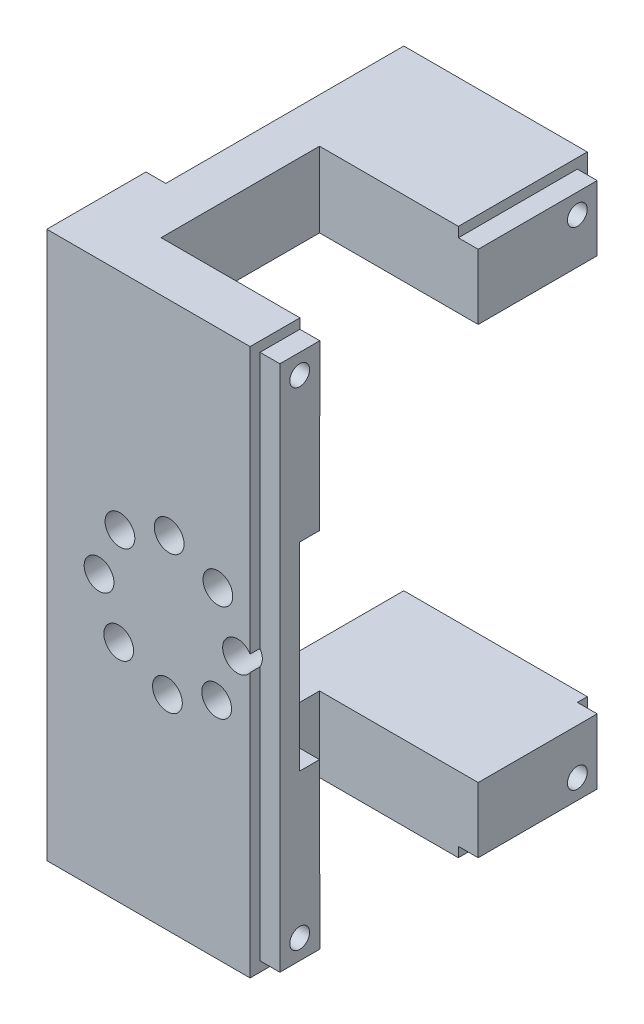
SolidWorks part; units mm, degrees
ref_plane "前视基准面" through (0, 0, 0) normal (0, 0, 1) x (1, 0, 0)
ref_plane "上视基准面" through (0, 0, 0) normal (0, 1, 0) x (1, 0, 0)
ref_plane "右视基准面" through (0, 0, 0) normal (1, 0, 0) x (0, 0, -1)
other "Configuration Table"
sketch "草图1" plane through (0, 0, 0) normal (0, 0, 1) x (1, 0, 0)
  line L0 (-1000, 0) -> (49000, 0) construction
  line L1 (-10.25, -20) -> (10.25, -20)
  line L2 (-10.25, -20) -> (-10.25, 20)
  line L3 (-10.25, 20) -> (10.25, 20)
  line L4 (10.25, -20) -> (10.25, 20)
  line L5 (-10.25, -20) -> (10.25, 20) construction
  line L6 (-10.25, 20) -> (10.25, -20) construction
  line L7 (-5, 15) -> (5, 15)
  line L8 (-5, 15) -> (-5, 25)
  line L9 (-5, 25) -> (5, 25)
  line L10 (5, 15) -> (5, 25)
  line L11 (-5, 15) -> (5, 25) construction
  line L12 (-5, 25) -> (5, 15) construction
  line L14 (-10.25, -35.1417) -> (10.25, -35.1417)
  line L15 (-10.25, -35.1417) -> (-10.25, 35.1417)
  line L16 (-10.25, 35.1417) -> (10.25, 35.1417)
  line L17 (10.25, -35.1417) -> (10.25, 35.1417)
  line L18 (-10.25, -35.1417) -> (10.25, 35.1417) construction
  line L19 (-10.25, 35.1417) -> (10.25, -35.1417) construction
  circle A0 centre (-5, 25) radius 2
  circle A1 centre (5, 25) radius 2
  circle A2 centre (5, -25) radius 2
  circle A3 centre (-5, -25) radius 2
  point P0 (0, 0)
  point P6 (0, 20)
  point P19 (0, 0)
  dimension "D5" = 4
  dimension "D6" = 4
  dimension "D1" = 20.5
  dimension "D2" = 40
  dimension "D3" = 10
  dimension "D4" = 10
extrude "凸台-拉伸1" add sketch "草图1" along normal blind 29 contours A1 L10 L3 L17 L16 L15 L8 A0 L9 | L14 L17 L1 L15 A2 A3 | A1 L9 A0 L8 L3 L10
sketch "草图2" plane through (0, 0, 29) normal (0, 0, 1) x (1, 0, 0)
  line L1 (-10.25, 35.1417) -> (10.25, 35.1417)
  line L2 (-10.25, 35.1417) -> (-10.25, -35.1417)
  line L3 (-10.25, -35.1417) -> (10.25, -35.1417)
  line L4 (10.25, 35.1417) -> (10.25, -35.1417)
extrude "凸台-拉伸2" add sketch "草图2" along normal blind 3
sketch "草图3" plane through (0, 0, 0) normal (0, 0, -1) x (-1, 0, 0)
  line L0 (-10.25, -35.1417) -> (-10.25, -20) construction
  line L1 (-10.25, -27.5709) -> (10.25, -27.5709)
  line L2 (-10.25, -27.5709) -> (-10.25, 27.5709)
  line L3 (-10.25, 27.5709) -> (10.25, 27.5709)
  line L4 (10.25, -27.5709) -> (10.25, 27.5709)
  line L5 (10.25, 20) -> (10.25, 35.1417) construction
  line L7 (-10.25, -35.1417) -> (10.25, -35.1417)
  line L8 (-10.25, -35.1417) -> (-10.25, 35.1417)
  line L9 (-10.25, 35.1417) -> (10.25, 35.1417)
  line L10 (10.25, -35.1417) -> (10.25, 35.1417)
  line M2 (-10.25, -35.1417) -> (10.25, -35.1417)
  line M3 (10.25, -35.1417) -> (10.25, -20)
  line M5 (-10.25, -20) -> (-10.25, -35.1417)
extrude "切除-拉伸1" cut sketch "草图3" against normal through all contours L1 M5 M2 M3 | L3 L10 L9 L8
sketch "草图5" plane through (0, -27.5709, 0) normal (0, -1, 0) x (1, 0, 0)
  line L0 (0, 0) -> (0, 2.5)
  circle A0 centre (0, 2.5) radius 2.5
  dimension "D2" = 5
  dimension "D1" = 2.5
extrude "凸台-拉伸3" add sketch "草图5" along normal blind 10
sketch "草图8" plane through (0, 27.5709, 0) normal (0, 1, 0) x (1, 0, 0)
  line L0 (0, 0) -> (0, -2.5)
  line L1 (0, -2.5) -> (0, -16.5)
  line L2 (0, -16.5) -> (0, -26.5)
  circle A0 centre (0, -16.5) radius 1.6
  circle A1 centre (0, -26.5) radius 1.6
  dimension "D4" = 3.2
  dimension "D5" = 3.2
  dimension "D1" = 2.5
  dimension "D2" = 14
  dimension "D3" = 10
extrude "切除-拉伸2" cut sketch "草图8" against normal up to next
sketch "草图9" plane through (0, -27.5709, 0) normal (0, -1, 0) x (1, 0, 0)
  line L1 (-10.25, 32) -> (10.25, 32)
  line L2 (-10.25, 32) -> (-10.25, 0)
  line L3 (-10.25, 0) -> (10.25, 0)
  line L4 (10.25, 32) -> (10.25, 0)
extrude "切除-拉伸3" cut sketch "草图9" along normal through all
sketch "草图12" plane through (0, 0, 0) normal (0, 0, -1) x (-1, 0, 0)
  line L1 (-10.25, 27.5709) -> (10.25, 27.5709)
  line L2 (-10.25, 27.5709) -> (-10.25, 20)
  line L3 (-10.25, 20) -> (10.25, 20)
  line L4 (10.25, 27.5709) -> (10.25, 20)
  circle A0 centre (-5, 25) radius 2
  circle A1 centre (5, 25) radius 2
extrude "凸台-拉伸5" add sketch "草图12" against normal blind 30
sketch "草图13" plane through (0, 27.5709, 0) normal (0, 1, 0) x (1, 0, 0)
  line L0 (0, 0) -> (0, -32)
  line L1 (10.25, -32) -> (-10.25, -32) construction
  line L2 (0, 0) -> (0, -10)
  line L3 (0, 0) -> (0, -2.5275)
  line L4 (0, 0) -> (0, -5)
  circle A2 centre (0, -5) radius 2.5
  circle A3 centre (0, -5) radius 4
  dimension "D3" = 5
  dimension "D4" = 5
  dimension "D5" = 8
  dimension "D1" = 32
  dimension "D2" = 10
extrude "凸台-拉伸6" add sketch "草图13" along normal blind 10 contours L4 A3 L2 A2 | L2 A3 L4 A2
sketch "草图15" plane through (0, 0, 0) normal (1, 0, 0) x (0, 0, -1)
  line L0 (-1, 27.5709) -> (0, 27.5709)
  line L1 (-1, 27.5709) -> (-1, 28.676)
  line L2 (-1, 27.5709) -> (-1, 37.5709) construction
  line L3 (-5, -962.4291) -> (-5, 49037.5709) construction
  line L4 (-2.5, 37.5709) -> (-7.5, 37.5709) construction
  arc A0 (-1, 28.676) -> (0, 27.5709) centre (0.1107, 28.676) ccw
  point P13 (-5, 37.5709)
revolve "旋转1" add sketch "草图15" angle 360 about L3
ref_plane "基准面1" through (0, 0, 5) normal (0, 0, 1) x (1, 0, 0)
sketch "草图16" plane through (0, 0, 5) normal (0, 0, 1) x (1, 0, 0)
  line L0 (0, 37.5709) -> (0, 33.5709)
  line L1 (2.5, 37.5709) -> (-2.5, 37.5709) construction
  circle A0 centre (0, 33.5709) radius 1.5
  dimension "D2" = 3
  dimension "D1" = 4
extrude "切除-拉伸5" cut sketch "草图16" against normal through all
sketch "草图17" plane through (0, 0, 0) normal (1, 0, 0) x (0, 0, -1)
  line L0 (-5, 37.5709) -> (-5, 33.5709)
  line L1 (-2.5, 37.5709) -> (-7.5, 37.5709) construction
  line L2 (-5, 11.275) -> (-5, -11.275) construction
  circle A0 centre (-5, 33.5709) radius 1.5
  dimension "D2" = 3
  dimension "D1" = 4
extrude "切除-拉伸6" cut sketch "草图17" against normal through all
sketch "草图19" plane through (0, -27.5709, 0) normal (0, -1, 0) x (1, 0, 0)
  line L0 (0, 0) -> (0, 5)
  line L1 (10.25, 0) -> (-10.25, 0) construction
  circle A0 centre (0, 5) radius 2.5
  circle A1 centre (0, 5) radius 4
  dimension "D2" = 5
  dimension "D3" = 8
  dimension "D1" = 5
extrude "凸台-拉伸7" add sketch "草图19" along normal blind 10
sketch "草图20" plane through (0, 0, 0) normal (1, 0, 0) x (0, 0, -1)
  line L0 (-1, -27.5709) -> (0, -27.5709)
  line L1 (-1, -27.5709) -> (-1, -28.5709)
  line L2 (-1, -37.5709) -> (-1, -27.5709) construction
  line L3 (-5, -1027.5709) -> (-5, 48972.4291) construction
  line L4 (-9, -27.5709) -> (-1, -27.5709) construction
  arc A0 (-1, -28.5709) -> (0, -27.5709) centre (0, -28.5709) cw
  point P13 (-5, -27.5709)
  dimension "D1" = 1
revolve "旋转2" add sketch "草图20" angle 360 about L3
sketch "草图21" plane through (0, 0, 5) normal (0, 0, 1) x (1, 0, 0)
  line L0 (0, -37.5709) -> (0, -33.5709)
  line L1 (-4, -37.5709) -> (4, -37.5709) construction
  circle A0 centre (0, -33.5709) radius 1.5
  dimension "D2" = 3
  dimension "D1" = 4
extrude "切除-拉伸7" cut sketch "草图21" against normal through all
sketch "草图22" plane through (0, 0, 0) normal (1, 0, 0) x (0, 0, -1)
  line L0 (-5, -37.5709) -> (-5, -33.5709)
  line L1 (-9, -37.5709) -> (-1, -37.5709) construction
  line L2 (-5, 11.275) -> (-5, -11.275) construction
  circle A0 centre (-5, -33.5709) radius 1.5
  dimension "D2" = 3
  dimension "D1" = 4
extrude "切除-拉伸8" cut sketch "草图22" against normal through all
sketch "草图23" plane through (0, 0, 32) normal (0, 0, 1) x (1, 0, 0)
  line L1 (-10.25, 27.5709) -> (10.25, 27.5709)
  line L2 (-10.25, 27.5709) -> (-10.25, -27.5709)
  line L3 (-10.25, -27.5709) -> (10.25, -27.5709)
  line L4 (10.25, 27.5709) -> (10.25, -27.5709)
extrude "凸台-拉伸8" add sketch "草图23" along normal blind 2
sketch "草图24" plane through (-10.25, 0, 0) normal (-1, 0, 0) x (0, 0, 1)
  line L0 (34, -27.5709) -> (0, -27.5709) construction
  line L1 (34, 27.5709) -> (24, 27.5709)
  line L2 (34, 27.5709) -> (34, -27.5709)
  line L3 (34, -27.5709) -> (24, -27.5709)
  line L4 (24, 27.5709) -> (24, -27.5709)
  dimension "D1" = 10
extrude "凸台-拉伸9" add sketch "草图24" along normal blind 2
sketch "草图25" plane through (10.25, 0, 0) normal (1, 0, 0) x (0, 0, -1)
  line L0 (-34, 27.5709) -> (-21, 27.5709)
  line L1 (-34, 27.5709) -> (0, 27.5709) construction
  line L2 (-21, 27.5709) -> (-17, 27.5709)
  line L3 (-17, 27.5709) -> (-17, -27.5709)
  line L6 (-17, -27.5709) -> (-25, -27.5709)
  line L7 (-34, -27.5709) -> (0, -27.5709) construction
  line L8 (-25, -27.5709) -> (-25, 27.5709)
  line M5 (-29, 20) -> (0, 20)
  line M7 (0, 27.5709) -> (-34, 27.5709)
  line M9 (-34, -27.5709) -> (0, -27.5709)
  line M11 (0, -20) -> (-29, -20)
  dimension "D1" = 13
  dimension "D2" = 4
  dimension "D3" = 8
extrude "切除-拉伸9" cut sketch "草图25" against normal blind 16 contours L8 L3 M9 M11 | L8 L3 M5 M7
sketch "草图26" plane through (0, 0, 29) normal (0, 0, -1) x (-1, 0, 0)
  circle A0 centre (-5, 25) radius 2
  circle A1 centre (5, 25) radius 2
  circle A2 centre (-5, -25) radius 2
  circle A3 centre (5, -25) radius 2
extrude "凸台-拉伸10" add sketch "草图26" along normal blind 20
sketch "草图27" plane through (0, -27.5709, 0) normal (0, -1, 0) x (1, 0, 0)
  line L1 (-5.75, 25) -> (10.25, 25)
  line L2 (-5.75, 25) -> (-5.75, 17)
  line L3 (-5.75, 17) -> (10.25, 17)
  line L4 (10.25, 25) -> (10.25, 17)
extrude "切除-拉伸10" cut sketch "草图27" against normal through all
sketch "草图29" plane through (10.25, 0, 0) normal (1, 0, 0) x (0, 0, -1)
  line L0 (-33, 26.5709) -> (-33, -26.5709)
  line L1 (-34, 27.5709) -> (0, 27.5709)
  line L2 (-34, 27.5709) -> (-34, -27.5709)
  line L3 (-34, -27.5709) -> (0, -27.5709)
  line L4 (0, 27.5709) -> (0, -27.5709)
  line L5 (-33, -26.5709) -> (-1, -26.5709)
  line L6 (-1, 26.5709) -> (-1, -26.5709)
  line L7 (-33, 26.5709) -> (-1, 26.5709)
  dimension "D1" = 1
extrude "切除-拉伸11" cut sketch "草图29" against normal blind 2
sketch "草图30" plane through (10.25, 0, 0) normal (1, 0, 0) x (0, 0, -1)
  line L1 (-34, 27.5709) -> (0, 27.5709)
  line L2 (-34, 27.5709) -> (-34, -27.5709)
  line L3 (-34, -27.5709) -> (0, -27.5709)
  line L4 (0, 27.5709) -> (0, -27.5709)
  dimension "D1" = 34
  dimension "D2" = 55.1417
sketch "草图32" plane through (10.25, 0, 0) normal (1, 0, 0) x (0, 0, -1)
  line L0 (-17, -26.5709) -> (-1, -26.5709) construction
  line L1 (-33, 26.5709) -> (-13, 26.5709)
  line L2 (-33, 26.5709) -> (-33, -26.5709)
  line L3 (-33, -26.5709) -> (-13, -26.5709)
  line L4 (-13, 26.5709) -> (-13, -26.5709)
  line L6 (-13, 26.5709) -> (-28.9769, 26.5709)
  line L7 (-13, 26.5709) -> (-13, -26.5709)
  line L8 (-13, -26.5709) -> (-28.9769, -26.5709)
  line L9 (-28.9769, 26.5709) -> (-28.9769, -26.5709)
  line L10 (-13, -26.5709) -> (-28.9769, -26.5709)
  line L11 (-13, -26.5709) -> (-13, 27.5939)
  line L12 (-13, 27.5939) -> (-28.9769, 27.5939)
  line L13 (-28.9769, -26.5709) -> (-28.9769, 27.5939)
  line L14 (-28.9769, 27.5939) -> (-13, 27.5939)
  line L15 (-28.9769, 27.5939) -> (-28.9769, -27.5919)
  line L16 (-28.9769, -27.5919) -> (-13, -27.5919)
  line L17 (-13, 27.5939) -> (-13, -27.5919)
  line M2 (-25, 26.5709) -> (-33, 26.5709)
  line M5 (-25, -26.5709) -> (-25, -20)
  line M6 (-25, -20) -> (-29, -20)
  line M8 (-29, 20) -> (-25, 20)
  line M9 (-25, 20) -> (-25, 26.5709)
  dimension "D1" = 20
extrude "切除-拉伸13" cut sketch "草图32" against normal blind 16 contours L9 L3 L4 L1 M8 M6 M5 M9 | L9 M2 M8 M9 | L9 L3 M6 M5 | L17 L3 L15 L16 | L13 L1 L11 L12 M2
sketch "草图33" plane through (10.25, 0, 0) normal (1, 0, 0) x (0, 0, -1)
  line L1 (-33, 26.5709) -> (-31, 26.5709)
  line L2 (-33, 26.5709) -> (-33, 24.5709)
  line L3 (-33, 24.5709) -> (-31, 24.5709)
  line L4 (-31, 26.5709) -> (-31, 24.5709)
  line L5 (-33, -26.5709) -> (-31, -26.5709)
  line L6 (-33, -26.5709) -> (-33, -24.5709)
  line L7 (-33, -24.5709) -> (-31, -24.5709)
  line L8 (-31, -26.5709) -> (-31, -24.5709)
  circle A0 centre (-31, 24.5709) radius 1
  circle A1 centre (-31, -24.5709) radius 1
  dimension "D3" = 2
  dimension "D6" = 2
  dimension "D1" = 2
  dimension "D2" = 2
  dimension "D4" = 2
  dimension "D5" = 2
extrude "切除-拉伸14" cut sketch "草图33" against normal blind 16 contours A1 | A0
sketch "草图35" plane through (10.25, 0, 0) normal (1, 0, 0) x (0, 0, -1)
  line L1 (-1, 26.5709) -> (-3, 26.5709)
  line L2 (-1, 26.5709) -> (-1, 24.5709)
  line L3 (-1, 24.5709) -> (-3, 24.5709)
  line L4 (-3, 26.5709) -> (-3, 24.5709)
  line L5 (-1, -26.5709) -> (-3, -26.5709)
  line L6 (-1, -26.5709) -> (-1, -24.5709)
  line L7 (-1, -24.5709) -> (-3, -24.5709)
  line L8 (-3, -26.5709) -> (-3, -24.5709)
  circle A0 centre (-3, 24.5709) radius 1
  circle A1 centre (-3, -24.5709) radius 1
  dimension "D3" = 2
  dimension "D6" = 2
  dimension "D1" = 2
  dimension "D2" = 2
  dimension "D4" = 2
  dimension "D5" = 2
extrude "切除-拉伸15" cut sketch "草图35" against normal blind 5 contours A1 | A0
sketch "草图36" plane through (0, -37.5709, 0) normal (0, -1, 0) x (1, 0, 0)
  circle A1 centre (0, 5) radius 2.65
  dimension "D1" = 5.3
extrude "切除-拉伸16" cut sketch "草图36" against normal blind 10
sketch "草图37" plane through (0, 37.5709, 0) normal (0, 1, 0) x (1, 0, 0)
  circle A0 centre (0, -5) radius 2.65
  dimension "D1" = 5.3
extrude "切除-拉伸17" cut sketch "草图37" against normal blind 10
sketch "草图38" plane through (0, 0, 29) normal (0, 0, -1) x (-1, 0, 0)
  line L0 (-10.25, 27.5709) -> (-10.25, -27.5709) construction
  line L1 (12.25, 27.5709) -> (-10.25, 27.5709)
  line L2 (12.25, 27.5709) -> (12.25, -27.5709)
  line L3 (12.25, -27.5709) -> (-10.25, -27.5709)
  line L4 (-10.25, 27.5709) -> (-10.25, -27.5709)
  line L5 (-10.25, 27.5709) -> (-10.25, -27.5709) construction
  line L7 (-67.737, 75.4855) -> (54.9645, 75.4855)
  line L8 (-67.737, 75.4855) -> (-67.737, -71.4355)
  line L9 (-67.737, -71.4355) -> (54.9645, -71.4355)
  line L10 (54.9645, 75.4855) -> (54.9645, -71.4355)
  point P13 (54.9645, -71.4355)
extrude "切除-拉伸18" cut sketch "草图38" along normal through all
sketch "草图39" plane through (0, 0, 29) normal (0, 0, -1) x (-1, 0, 0)
  line L1 (-5, -5) -> (5, -5)
  line L2 (-5, -5) -> (-5, 5)
  line L3 (-5, 5) -> (5, 5)
  line L4 (5, -5) -> (5, 5)
  line L5 (-5, -5) -> (5, 5) construction
  line L6 (-5, 5) -> (5, -5) construction
  circle A0 centre (0, 0) radius 4
  circle A1 centre (-5, 4.876) radius 1.5
  circle A2 centre (4.876, 5) radius 1.5
  circle A3 centre (5, -4.876) radius 1.5
  circle A4 centre (-4.876, -5) radius 1.5
  circle A5 centre (-0.0877, 6.9834) radius 1.5
  circle A6 centre (4.876, 5) radius 1.5
  circle A7 centre (6.9834, 0.0877) radius 1.5
  circle A8 centre (5, -4.876) radius 1.5
  circle A9 centre (0.0877, -6.9834) radius 1.5
  circle A10 centre (-4.876, -5) radius 1.5
  circle A11 centre (-6.9834, -0.0877) radius 1.5
  point P0 (0, 0)
  point P19 (0, 0)
  point P34 (0, 0)
  dimension "D3" = 8
  dimension "D4" = 3
  dimension "D1" = 10
  dimension "D2" = 10
  dimension "D5" = 4
  dimension "D6" = 8
extrude "切除-拉伸22" cut sketch "草图39" against normal blind 5 contours A7 | A9 | A11 | A1 | A5 | A2 | A3 | A4
sketch "草图41" plane through (0, 0, 29) normal (0, 0, -1) x (-1, 0, 0)
  line L0 (-10.25, 27.5709) -> (-10.25, -27.5709) construction
  line L1 (10.25, -10) -> (-10.25, -10)
  line L2 (10.25, -10) -> (10.25, 10)
  line L3 (10.25, 10) -> (-10.25, 10)
  line L4 (-10.25, -10) -> (-10.25, 10)
  line L5 (10.25, -10) -> (-10.25, 10) construction
  line L6 (10.25, 10) -> (-10.25, -10) construction
  point P0 (0, 0)
  dimension "D1" = 20
extrude "切除-拉伸23" cut sketch "草图41" against normal blind 2
